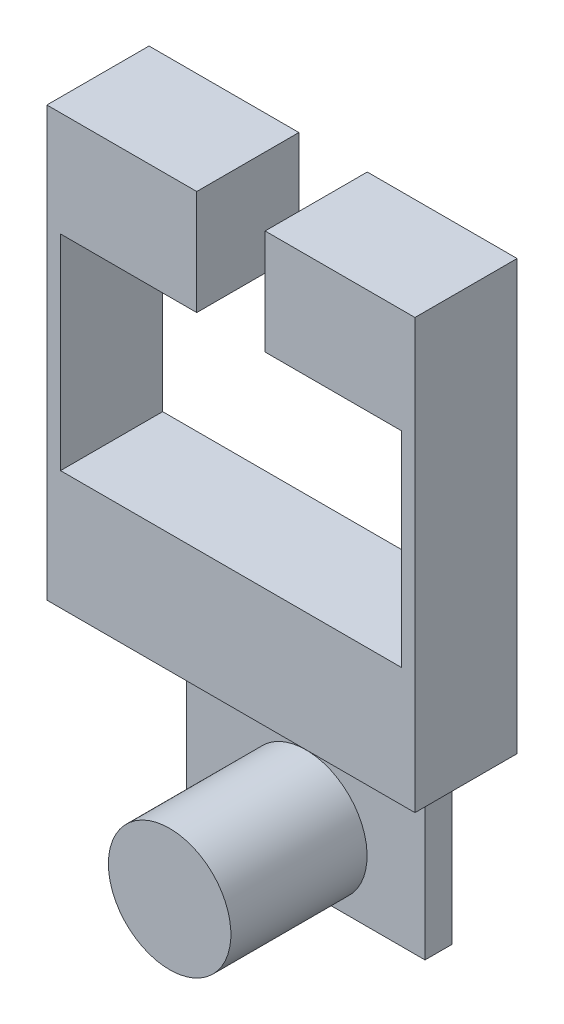
SolidWorks part; units mm, degrees
material "FEA Aluminum"
ref_plane "Front Plane" through (0, 0, 0) normal (0, 0, 1) x (1, 0, 0)
ref_plane "Top Plane" through (0, 0, 0) normal (0, 1, 0) x (1, 0, 0)
ref_plane "Right Plane" through (0, 0, 0) normal (1, 0, 0) x (0, 0, -1)
sketch "Sketch1" plane through (0, 0, 0) normal (0, 0, 1) x (1, 0, 0)
  line L1 (-34.3205, 79.975) -> (34.3205, 79.975)
  line L2 (-34.3205, 79.975) -> (-34.3205, 0)
  line L3 (-34.3205, 0) -> (34.3205, 0)
  line L4 (34.3205, 79.975) -> (34.3205, 0)
  dimension "D1" = 68.641
  dimension "D2" = 79.975
extrude "Main-Body" add sketch "Sketch1" along normal mid plane 19.05
sketch "Sketch2" plane through (0, 0, 9.525) normal (0, 0, 1) x (1, 0, 0)
  line L0 (0, 84.5954) -> (0, -7.8995) construction
  line L1 (-34.3205, 0) -> (34.3205, 0) construction
  line L2 (-31.7805, 60.417) -> (31.7805, 60.417)
  line L3 (-31.7805, 60.417) -> (-31.7805, 22.19)
  line L4 (-31.7805, 22.19) -> (31.7805, 22.19)
  line L5 (31.7805, 60.417) -> (31.7805, 22.19)
  dimension "D1" = 63.561
  dimension "D2" = 38.227
  dimension "D3" = 22.19
extrude "Lower-T-Cavity" cut sketch "Sketch2" against normal through all
sketch "Sketch3" plane through (0, 0, 9.525) normal (0, 0, 1) x (1, 0, 0)
  line L0 (0, 84.1431) -> (0, -5.638) construction
  line L1 (31.7805, 60.417) -> (-31.7805, 60.417) construction
  line L2 (-6.3754, 79.975) -> (6.3754, 79.975)
  line L3 (-6.3754, 79.975) -> (-6.3754, 60.417)
  line L4 (-6.3754, 60.417) -> (6.3754, 60.417)
  line L5 (6.3754, 79.975) -> (6.3754, 60.417)
  line L6 (34.3205, 79.975) -> (-34.3205, 79.975) construction
  dimension "D1" = 12.7508
extrude "Top-Slot" cut sketch "Sketch3" against normal through all
sketch "Sketch4" plane through (0, 0, -9.525) normal (0, 0, -1) x (-1, 0, 0)
  line L0 (0, 84.5954) -> (0, -5.9773) construction
  line L1 (34.3205, 0) -> (-34.3205, 0) construction
  line L2 (-22.225, 0) -> (22.225, 0)
  line L3 (-22.225, 0) -> (-22.225, -36.8236)
  line L4 (-22.225, -36.8236) -> (22.225, -36.8237)
  line L5 (22.225, 0) -> (22.225, -36.8237)
  dimension "D1" = 44.45
  dimension "D2" = 36.8236
extrude "Hanger" add sketch "Sketch4" against normal blind 5.08
sketch "Sketch5" plane through (0, 0, -9.525) normal (0, 0, -1) x (-1, 0, 0)
  circle A0 centre (0, -25.4) radius 11.4236
  dimension "D2" = 22.8473
  dimension "D1" = 25.4
extrude "Strap-Pin" add sketch "Sketch5" against normal blind 30.48
equation "\"Bracket_depth\"= 0.750in"
equation "\"Pin_diameter\"= 0.8995in"
equation "\"Pin_free_length\"= 1.000in"
equation "\"Hanger_width\"= 0.750in"
equation "\"Hanger_thickness\"= 0.2000in"
equation "\"Hanger_length\"= 1.000in"
equation "\"Web_thickness\"= 0.100in"
equation "\"Lip_height\"= 0.770in"
equation "\"Top_slot_width\"= 0.5020in"
equation "\"T_cavity_width\"= 2.5024in"
equation "\"T_cavity_height\"= 1.5050in"
equation "\"Crossmember_height\"= ( 3 * 1400 * 2.6024 / ( 2 * 0.75 * 10000 ) ) ^ ( 1 / 2 ) * 1in + 0.020in"
equation "\"D1@Sketch1\"=\"T_cavity_width\"+2*\"Web_thickness\""
equation "\"D2@Sketch1\"=\"Crossmember_height\"+\"T_cavity_height\"+\"Lip_height\""
equation "\"D1@Main-Body\" = \"Bracket_depth\""
equation "\"D1@Sketch2\"=\"T_cavity_width\""
equation "\"D2@Sketch2\"=\"T_cavity_height\""
equation "\"D3@Sketch2\"=\"Crossmember_height\""
equation "\"D1@Sketch3\"=\"Top_slot_width\""
equation "\"D2@Sketch4\"=\"Hanger_length\"+\"Pin_diameter\"/2"
equation "\"D1@Hanger\" = \"Hanger_thickness\""
equation "\"D1@Sketch5\"=\"Hanger_length\""
equation "\"D2@Sketch5\"=\"Pin_diameter\""
equation "\"D1@Strap-Pin\" = \"Pin_free_length\" + \"Hanger_thickness\""
